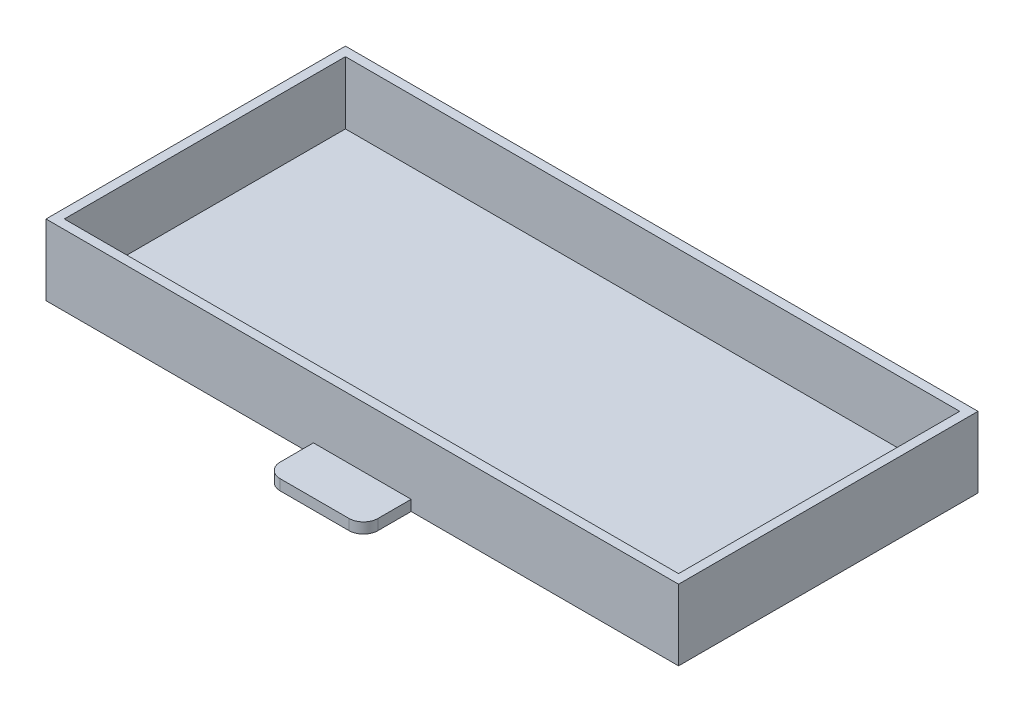
SolidWorks part; units mm, degrees
ref_plane "Front Plane" through (0, 0, 0) normal (0, 0, 1) x (1, 0, 0)
ref_plane "Top Plane" through (0, 0, 0) normal (0, 1, 0) x (1, 0, 0)
ref_plane "Right Plane" through (0, 0, 0) normal (1, 0, 0) x (0, 0, -1)
sketch "Sketch2" plane through (0, 0, 0) normal (0, 1, 0) x (1, 0, 0)
  line L0 (0, 31.1) -> (0, -31.1) construction
  line L1 (-65.7, 31.1) -> (65.7, 31.1)
  line L2 (-65.7, 31.1) -> (-65.7, -31.1)
  line L3 (-65.7, -31.1) -> (65.7, -31.1)
  line L4 (65.7, 31.1) -> (65.7, -31.1)
  line L5 (-65.7, 0) -> (65.7, 0) construction
  point P8 (0, 0)
  dimension "D1" = 131.4
  dimension "D2" = 62.2
extrude "Boss-Extrude1" add sketch "Sketch2" along normal blind 14.7
sketch "Sketch3" plane through (0, 14.7, 0) normal (0, 1, 0) x (1, 0, 0)
  line L0 (-65.7, 31.1) -> (-65.7, -31.1) construction
  line L1 (-63.8, 29.2) -> (63.8, 29.2)
  line L2 (-63.8, 29.2) -> (-63.8, -29.2)
  line L3 (-63.8, -29.2) -> (63.8, -29.2)
  line L4 (63.8, 29.2) -> (63.8, -29.2)
  line L5 (-65.7, -31.1) -> (65.7, -31.1) construction
  line L6 (65.7, 31.1) -> (-65.7, 31.1) construction
  line L7 (65.7, -31.1) -> (65.7, 31.1) construction
  dimension "D1" = 1.9
  dimension "D2" = 1.9
  dimension "D3" = 1.9
  dimension "D4" = 1.9
extrude "Cut-Extrude1" cut sketch "Sketch3" against normal blind 13
sketch "Sketch4" plane through (0, 0, 0) normal (0, -1, 0) x (1, 0, 0)
  line L0 (0, 31.1) -> (0, -31.1) construction
  line L1 (-65.7, 31.1) -> (65.7, 31.1) construction
  line L2 (65.7, -31.1) -> (-65.7, -31.1) construction
  line L4 (-10.15, 31.1) -> (10.15, 31.1)
  line L5 (-10.15, 31.1) -> (-10.15, 41)
  line L6 (-10.15, 41) -> (10.15, 41)
  line L7 (10.15, 31.1) -> (10.15, 41)
  dimension "D1" = 20.3
  dimension "D2" = 10.15
  dimension "D3" = 9.9
extrude "Boss-Extrude2" add sketch "Sketch4" against normal blind 2.2
fillet "Fillet1" radius 3 2 edges at (-10.15, 1.1, 41) (10.15, 1.1, 41)
equation "\"D3@Sketch3\"=\"D1@Sketch3\""
equation "\"D4@Sketch3\"=\"D1@Sketch3\""
equation "\"D2@Sketch4\"=\"D1@Sketch4\"/2"
